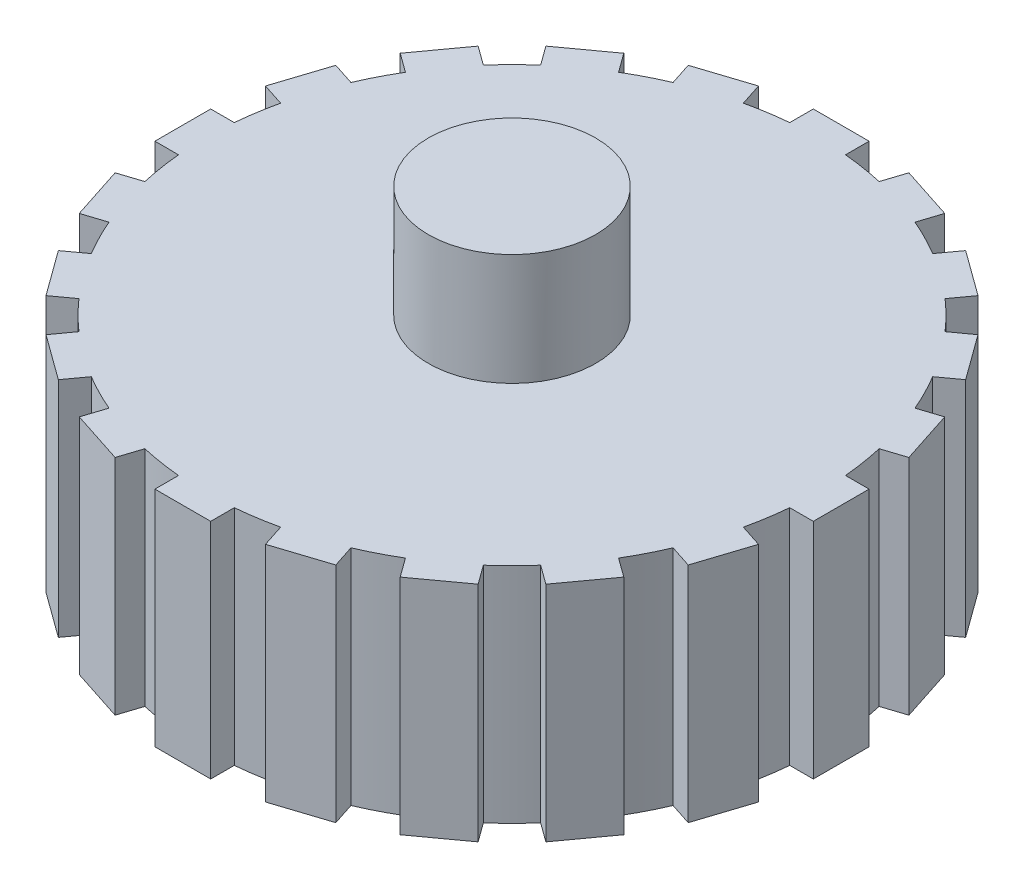
SolidWorks part; units mm, degrees
ref_plane "Plan de face" through (0, 0, 0) normal (0, 0, 1) x (1, 0, 0)
ref_plane "Plan de dessus" through (0, 0, 0) normal (0, 1, 0) x (1, 0, 0)
ref_plane "Plan de droite" through (0, 0, 0) normal (1, 0, 0) x (0, 0, -1)
sketch "Esquisse1" plane through (0, 0, 0) normal (0, 1, 0) x (1, 0, 0)
  circle A0 centre (0, 0) radius 7.5
  dimension "D1" = 15
extrude "Boss.-Extru.1" add sketch "Esquisse1" along normal blind 40
ref_plane "Plan1" through (0, 10, 0) normal (0, -1, 0) x (-1, 0, 0)
sketch "Esquisse2" plane through (0, 10, 0) normal (0, -1, 0) x (-1, 0, 0)
  circle A0 centre (0, 0) radius 27.5
  dimension "D1" = 55
extrude "Boss.-Extru.2" add sketch "Esquisse2" against normal blind 20
ref_plane "Plan2" through (0, 0, 22.5) normal (0, 0, 1) x (1, 0, 0)
sketch "Esquisse3" plane through (0, 0, 22.5) normal (0, 0, 1) x (1, 0, 0)
  line L0 (0, 10) -> (0, 30) construction
  line L1 (-5.5, 10) -> (5.5, 10) construction
  line L2 (27.5, 30) -> (-27.5, 30) construction
  line L4 (-2.5, 10) -> (2.5, 10)
  line L5 (-2.5, 10) -> (-2.5, 30)
  line L6 (-2.5, 30) -> (2.5, 30)
  line L7 (2.5, 10) -> (2.5, 30)
  line L8 (-2.5, 10) -> (2.5, 30) construction
  line L9 (-2.5, 30) -> (2.5, 10) construction
  point P6 (0, 20)
  dimension "D1" = 5
extrude "Boss.-Extru.3" add sketch "Esquisse3" along normal blind 7
pattern_circular "Répétition circulaire1" count 20 over 360 about axis through (0, 0, 0) along (0, 1, 0) of "Boss.-Extru.3"
